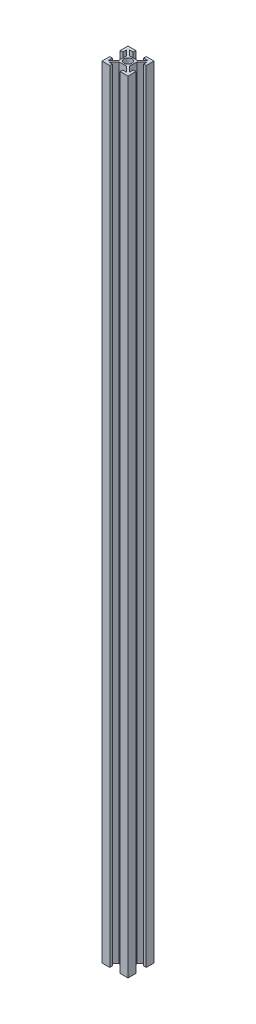
SolidWorks part; units mm, degrees
material "1060 Alloy"
ref_plane "Front Plane" through (0, 0, 0) normal (0, 0, 1) x (1, 0, 0)
ref_plane "Top Plane" through (0, 0, 0) normal (0, 1, 0) x (1, 0, 0)
ref_plane "Right Plane" through (0, 0, 0) normal (1, 0, 0) x (0, 0, -1)
sketch "2020 sketch" plane through (0, 0, 0) normal (0, 1, 0) x (1, 0, 0)
  line L0 (-4, 10) -> (-4, 8)
  line L1 (-10, 10) -> (-4, 10)
  line L2 (-10, 10) -> (-10, 4)
  line L3 (-10, -10) -> (-4, -10)
  line L4 (10, 10) -> (10, 4)
  line L5 (-10, 10) -> (10, -10) construction
  line L6 (-10, -10) -> (10, 10) construction
  line L7 (-4, 8) -> (-7, 8)
  line L8 (-7, 8) -> (-3, 4)
  line L9 (-3, 4) -> (3, 4)
  line L10 (3, 4) -> (7, 8)
  line L11 (7, 8) -> (4, 8)
  line L12 (4, 8) -> (4, 10)
  line L13 (4, 3) -> (4, -3)
  line L14 (8, 7) -> (4, 3)
  line L15 (8, 4) -> (8, 7)
  line L16 (10, 4) -> (8, 4)
  line L17 (8, -4) -> (10, -4)
  line L18 (8, -7) -> (8, -4)
  line L19 (4, -3) -> (8, -7)
  line L20 (3, -4) -> (-3, -4)
  line L21 (7, -8) -> (3, -4)
  line L22 (4, -8) -> (7, -8)
  line L23 (4, -10) -> (4, -8)
  line L24 (-4, -8) -> (-4, -10)
  line L25 (-7, -8) -> (-4, -8)
  line L26 (-3, -4) -> (-7, -8)
  line L27 (-4, -3) -> (-4, 3)
  line L28 (-8, -7) -> (-4, -3)
  line L29 (-8, -4) -> (-8, -7)
  line L30 (-10, -4) -> (-8, -4)
  line L31 (-8, 4) -> (-10, 4)
  line L32 (-8, 7) -> (-8, 4)
  line L33 (-4, 3) -> (-8, 7)
  line L34 (-10, -4) -> (-10, -10)
  line L35 (10, -4) -> (10, -10)
  line L36 (4, 10) -> (10, 10)
  line L37 (4, -10) -> (10, -10)
  circle A0 centre (0, 0) radius 3
  point P0 (0, 0)
  point P14 (4, 9)
  point P42 (0, 0)
  dimension "D9" = 6
  dimension "D1" = 20
  dimension "D2" = 20
  dimension "D3" = 8
  dimension "D4" = 6
  dimension "D5" = 6
  dimension "D6" = 2
  dimension "D7" = 4
  dimension "D8" = 4
extrude "Boss-Extrude1" add sketch "2020 sketch" along normal blind 600 contours A0 | L28 L27 L33 L32 L31 L2 L1 L0 L7 L8 L9 L10 L11 L12 L36 L4 L16 L15 L14 L13 L19 L18 L17 L35 L37 L23 L22 L21 L20 L26 L25 L24 L3 L34 L30 L29
